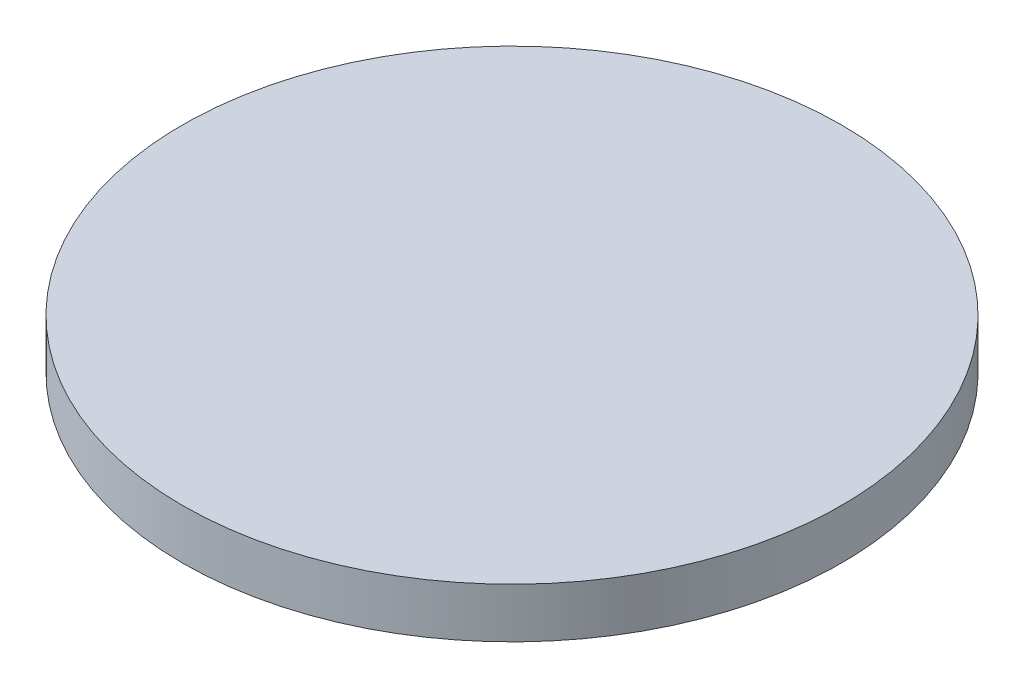
SolidWorks part; units mm, degrees
material "6061-T6 (SS)"
ref_plane "Front" through (0, 0, 0) normal (0, 0, 1) x (1, 0, 0)
ref_plane "Top" through (0, 0, 0) normal (0, 1, 0) x (1, 0, 0)
ref_plane "Right" through (0, 0, 0) normal (1, 0, 0) x (0, 0, -1)
sketch "Sketch1" plane through (0, 0, 0) normal (0, 1, 0) x (1, 0, 0)
  line L1 (0, 0) -> (127.635, 0)
  line L2 (0, 0) -> (0, 127.635)
  line L3 (0, 127.635) -> (127.635, 127.635)
  line L4 (127.635, 0) -> (127.635, 127.635)
  dimension "D1" = 127.635
  dimension "D2" = 127.635
extrude "Main Plate" add sketch "Sketch1" along normal blind 12.7
sketch "Sketch9" plane through (0, 12.7, 0) normal (0, 1, 0) x (1, 0, 0)
  circle A0 centre (63.8175, 63.8175) radius 85.725
  dimension "D1" = 171.45
extrude "Boss-Extrude1" add sketch "Sketch9" against normal up to surface (12.7 mm away) contours A0 up to face at (63.8175, 0, -63.8175)
sketch "Sketch10" plane through (0, 12.7, 0) normal (0, 1, 0) x (1, 0, 0)
  circle A0 centre (63.8175, 63.8175) radius 97.0396
  circle A1 centre (63.8175, 63.8175) radius 83.82
extrude "Cut-Extrude1" cut sketch "Sketch10" against normal blind 167.64 contours A0 | A1
sketch "Sketch11" plane through (0, 12.7, 0) normal (0, 1, 0) x (1, 0, 0)
  circle A0 centre (63.8175, 63.8175) radius 38.4175 construction
  circle A1 centre (63.8175, 63.8175) radius 42.8813 construction
  circle A2 centre (63.8175, 63.8175) radius 48.0528 construction
  circle A3 centre (63.8175, 63.8175) radius 83.82 construction
  dimension "D1" = 76.835
  dimension "D2" = 85.7626
  dimension "D3" = 96.1055
sketch "Sketch12" plane through (0, 12.7, 0) normal (0, 1, 0) x (1, 0, 0)
  line L0 (63.8175, 156.3529) -> (63.8175, -30.2474) construction
  line L1 (160.3603, 63.0527) -> (-31.9911, 63.0527) construction
  point P6 (63.8175, 63.0527)
sketch "Sketch2" plane through (0, 12.7, 0) normal (0, 1, 0) x (1, 0, 0)
  circle A0 centre (46.355, 108.585) radius 3.556
  circle A3 centre (63.8175, 63.8175) radius 48.0528 construction
  dimension "D1" = 7.112
extrude "U-Bolt Hole" [suppressed] cut sketch "Sketch2" against normal blind 12.7
pattern_linear "U-Bolt Pattern" [suppressed] count 2 spacing 34.925 along (-1, 0, 0)
sketch "Sketch3" [suppressed] plane through (0, 12.7, 0) normal (0, 1, 0) x (1, 0, 0)
  circle A0 centre (25.4, 44.7675) radius 1.778
  circle A1 centre (63.8175, 63.8175) radius 42.8813 construction
  dimension "D1" = 3.556
extrude "Raptor Bolt Hole" [suppressed] cut sketch "Sketch3" against normal blind 12.7
pattern_linear "Raptor Bolt Pattern" [suppressed] count 2 spacing 38.1 along (0, 0, 1) count 2 spacing 76.835 along (-1, 0, 0)
sketch "Sketch4" [suppressed] plane through (0, 12.7, 0) normal (0, 1, 0) x (1, 0, 0)
  circle A0 centre (25.4, 63.8175) radius 12.7
  circle A1 centre (63.8175, 63.8175) radius 38.4175 construction
  dimension "D1" = 25.4
extrude "Co2 Cylinder Hole" [suppressed] cut sketch "Sketch4" against normal blind 12.7
pattern_linear "Co2 Pattern" [suppressed] count 2 spacing 76.835 along (-1, 0, 0)
sketch "Sketch13" plane through (0, 12.7, 0) normal (0, 1, 0) x (1, 0, 0)
  line L0 (63.8175, 156.3529) -> (63.8175, -30.2474) construction
  circle A0 centre (63.8175, 21.1558) radius 1.905
  dimension "D1" = 3.81
extrude "Cut-Extrude2" [suppressed] cut sketch "Sketch13" against normal up to surface (12.7 mm away)
sketch "Sketch14" plane through (0, 12.7, 0) normal (0, 1, 0) x (1, 0, 0)
  line L0 (201.1692, 63.8175) -> (-73.4523, 63.8175) construction
ref_plane "Plane1" through (0, 0, -63.8175) normal (0, 0, -1) x (-1, 0, 0)
ref_plane "Plane2" through (-20.0025, 0, 0) normal (-1, 0, 0) x (0, 0, 1)
sketch "Sketch15" plane through (-20.0025, 0, 0) normal (-1, 0, 0) x (0, 0, 1)
  line L0 (-63.8175, 92.202) -> (-63.8175, -92.202) construction
  line L1 (20.0025, 12.7) -> (-147.6375, 12.7) construction
  circle A0 centre (-63.8175, 6.35) radius 1.4351
  dimension "D1" = 2.8702
  dimension "D2" = 6.35
extrude "Cut-Extrude3" [suppressed] cut sketch "Sketch15" against normal blind 15.24
pattern_circular "CirPattern1" [suppressed] count 12 over 360
sketch "Sketch16" plane through (0, 12.7, 0) normal (0, 1, 0) x (1, 0, 0)
  line L0 (63.8175, 63.8175) -> (123.0872, 123.0872) construction
  line L1 (63.8175, 63.8175) -> (123.0872, 4.5478) construction
  line L2 (92.202, 63.8175) -> (-92.202, 63.8175) construction
  line L3 (107.3987, 20.2363) -> (111.8888, 15.7462)
  line L4 (108.6773, 108.6773) -> (113.1913, 113.1913)
  circle A0 centre (63.8175, 63.8175) radius 83.82 construction
  arc A1 (113.1913, 113.1913) -> (111.8888, 15.7462) centre (62.4974, 65.1376) cw
  arc A2 (108.6773, 108.6773) -> (107.3987, 20.2363) centre (62.4754, 65.1156) cw
  dimension "D3" = 69.85
  dimension "D4" = 63.5
  dimension "D1" = 45
  dimension "D2" = 90
  dimension "D5" = 6.35
  dimension "D6" = 6.3837
extrude "Cut-Extrude4" [suppressed] cut sketch "Sketch16" against normal blind 15.24
